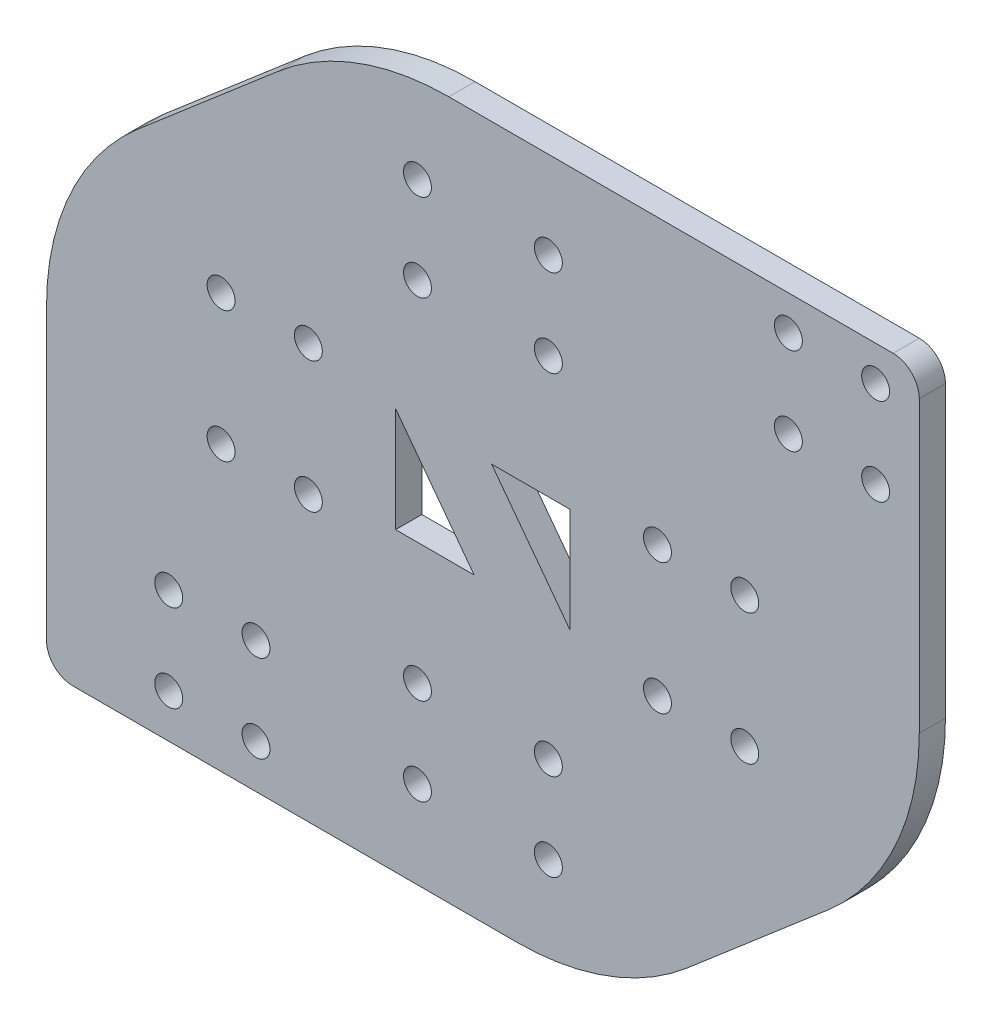
SolidWorks part; units mm, degrees
ref_plane "前视基准面" through (0, 0, 0) normal (0, 0, 1) x (1, 0, 0)
ref_plane "上视基准面" through (0, 0, 0) normal (0, 1, 0) x (1, 0, 0)
ref_plane "右视基准面" through (0, 0, 0) normal (1, 0, 0) x (0, 0, -1)
other "Configuration Table"
sketch "草图1" plane through (0, 0, 0) normal (0, 0, 1) x (1, 0, 0)
  line L1 (0, 0) -> (100, 0)
  line L2 (0, 0) -> (0, -80)
  line L3 (0, -80) -> (100, -80)
  line L4 (100, 0) -> (100, -80)
  dimension "D1" = 100
  dimension "D2" = 80
extrude "凸台-拉伸1" add sketch "草图1" along normal blind 3
sketch "草图2" plane through (0, 0, 3) normal (0, 0, 1) x (1, 0, 0)
  line L0 (50, 0) -> (50, -80) construction
  line L1 (100, 0) -> (0, 0) construction
  line L2 (0, -80) -> (100, -80) construction
  line L3 (100, -40) -> (0, -40) construction
  line L4 (100, -80) -> (100, 0) construction
  line L5 (0, 0) -> (0, -80) construction
  line L6 (0, -15) -> (100, -15) construction
  line L7 (25, 0) -> (25, -80) construction
  line L8 (19, -80) -> (19, 0) construction
  line L9 (50, -70) -> (0, -70) construction
  line L10 (100, -9) -> (0, -9) construction
  line L11 (90, 0) -> (90, -9) construction
  line L12 (35, 0) -> (0, -30)
  line L13 (0, -30) -> (0, 0)
  line L14 (0, 0) -> (35, 0)
  line L15 (100, -80) -> (100, -50)
  line L16 (100, -50) -> (65, -80)
  line L17 (65, -80) -> (100, -80)
  line L18 (40, -34) -> (40, -46)
  line L19 (40, -46) -> (49, -46)
  line L20 (49, -46) -> (40, -34)
  line L21 (51, -34) -> (60, -46)
  line L22 (60, -46) -> (60, -34)
  line L23 (60, -34) -> (51, -34)
  circle A0 centre (42.5, -10) radius 1.6
  circle A1 centre (57.5, -10) radius 1.6
  circle A2 centre (57.5, -20) radius 1.6
  circle A3 centre (42.5, -20) radius 1.6
  circle A4 centre (42.5, -60) radius 1.6
  circle A5 centre (57.5, -60) radius 1.6
  circle A6 centre (57.5, -70) radius 1.6
  circle A7 centre (42.5, -70) radius 1.6
  circle A8 centre (20, -32.5) radius 1.6
  circle A9 centre (30, -32.5) radius 1.6
  circle A10 centre (30, -47.5) radius 1.6
  circle A11 centre (20, -47.5) radius 1.6
  circle A12 centre (80, -47.5) radius 1.6
  circle A13 centre (70, -47.5) radius 1.6
  circle A14 centre (70, -32.5) radius 1.6
  circle A15 centre (80, -32.5) radius 1.6
  circle A16 centre (14, -65) radius 1.6
  circle A17 centre (24, -65) radius 1.6
  circle A18 centre (24, -75) radius 1.6
  circle A19 centre (14, -75) radius 1.6
  circle A20 centre (95, -4) radius 1.6
  circle A21 centre (85, -4) radius 1.6
  circle A22 centre (95, -14) radius 1.6
  circle A23 centre (85, -14) radius 1.6
  point P85 (0, 0)
  point P87 (0, 0)
  point P88 (0, 0)
  dimension "D1" = 3.2
  dimension "D5" = 7.5
  dimension "D7" = 3.2
  dimension "D10" = 3.2
  dimension "D15" = 10
  dimension "D18" = 3.2
  dimension "D2" = 7.5
  dimension "D3" = 5
  dimension "D4" = 25
  dimension "D6" = 5
  dimension "D8" = 25
  dimension "D9" = 31
  dimension "D11" = 5
  dimension "D12" = 5
  dimension "D13" = 10
  dimension "D14" = 31
  dimension "D16" = 5
  dimension "D17" = 5
  dimension "D19" = 35
  dimension "D20" = 30
  dimension "D21" = 30
  dimension "D22" = 35
  dimension "D23" = 9
  dimension "D24" = 12
  dimension "D25" = 6
  dimension "D26" = 10
  dimension "D27" = 12
  dimension "D28" = 9
extrude "切除-拉伸1" cut sketch "草图2" against normal through all
fillet "圆角1" radius 30 2 edges at (100, -50, 1.5) (0, -30, 1.5)
fillet "圆角2" radius 30 2 edges at (35, 0, 1.5) (65, -80, 1.5)
fillet "圆角3" radius 3 2 edges at (0, -80, 1.5) (100, 0, 1.5)
